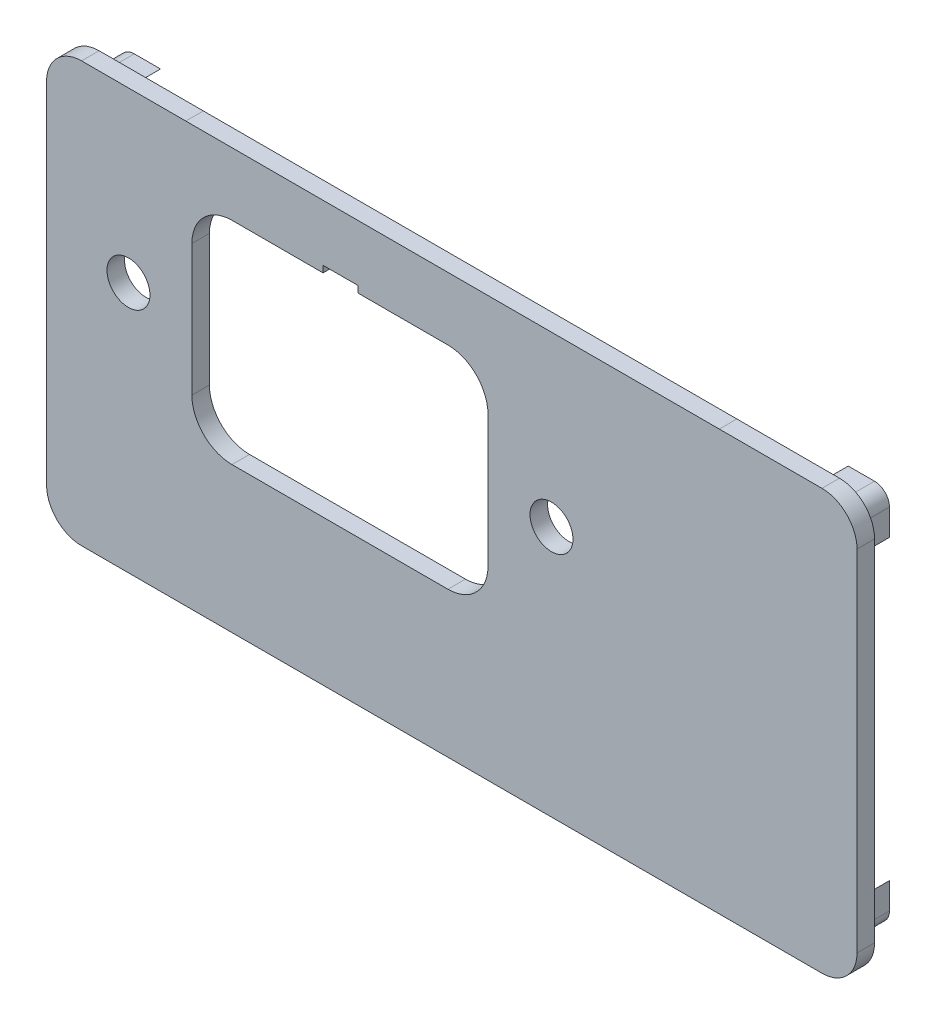
SolidWorks part; units mm, degrees
ref_plane "Front Plane" through (0, 0, 0) normal (0, 0, 1) x (1, 0, 0)
ref_plane "Top Plane" through (0, 0, 0) normal (0, 1, 0) x (1, 0, 0)
ref_plane "Right Plane" through (0, 0, 0) normal (1, 0, 0) x (0, 0, -1)
sketch "Sketch1" plane through (0, 0, 0) normal (0, 0, 1) x (1, 0, 0)
  line L6 (9.1686, 76.7653) -> (-2.7153, 76.7653)
  line L7 (70.0331, 76.7655) -> (9.1686, 76.7653)
  line L8 (81.7397, 76.7655) -> (70.0331, 76.7655)
  line L9 (85.7397, 32.8565) -> (85.7397, 72.7655)
  line L10 (-2.7153, 28.8565) -> (81.7397, 28.8565)
  line L11 (-6.7153, 72.7653) -> (-6.7153, 32.8565)
  line L18 (36.0228, 69.5903) -> (39.0739, 69.5903)
  line L19 (43.6459, 65.0183) -> (43.6459, 50.0323)
  line L20 (39.0739, 45.4603) -> (36.0228, 45.4603)
  line L21 (17.487, 45.4603) -> (14.4359, 45.4603)
  line L22 (9.8639, 50.0323) -> (9.8639, 65.0183)
  line L23 (14.4359, 69.5903) -> (17.487, 69.5903)
  line L24 (17.487, 69.5903) -> (24.826, 69.5903)
  line L25 (36.0228, 45.4603) -> (17.487, 45.4603)
  line L27 (24.826, 69.5903) -> (24.826, 70.3403)
  line L28 (24.826, 70.3403) -> (28.826, 70.3403)
  line L29 (28.826, 70.3403) -> (28.826, 69.5903)
  line L30 (28.826, 69.5903) -> (36.0228, 69.5903)
  circle A6 centre (50.8849, 57.5253) radius 2.449
  circle A7 centre (2.6249, 57.5253) radius 2.449
  arc A8 (85.7397, 72.7655) -> (81.7397, 76.7655) centre (81.7397, 72.7655) ccw
  arc A9 (81.7397, 28.8565) -> (85.7397, 32.8565) centre (81.7397, 32.8565) ccw
  arc A10 (-6.7153, 32.8565) -> (-2.7153, 28.8565) centre (-2.7153, 32.8565) ccw
  arc A11 (-2.7153, 76.7653) -> (-6.7153, 72.7653) centre (-2.7153, 72.7653) ccw
  arc A16 (43.6459, 65.0183) -> (39.0739, 69.5903) centre (39.0739, 65.0183) ccw
  arc A17 (39.0739, 45.4603) -> (43.6459, 50.0323) centre (39.0739, 50.0323) ccw
  arc A18 (9.8639, 50.0323) -> (14.4359, 45.4603) centre (14.4359, 50.0323) ccw
  arc A19 (14.4359, 69.5903) -> (9.8639, 65.0183) centre (14.4359, 65.0183) ccw
extrude "Boss-Extrude2" add sketch "Sketch1" along normal blind 2
sketch "Sketch2" plane through (0, 0, 0) normal (0, 0, -1) x (-1, 0, 0)
  line L3 (-70.0331, 76.7655) -> (-9.1686, 76.7653) construction
  line L6 (4.4153, 35.8565) -> (4.4153, 32.8565)
  line L8 (-9.1686, 74.4653) -> (2.7153, 74.4653) construction
  line L9 (-70.0331, 76.7655) -> (-9.1686, 76.7653)
  line L10 (-81.7397, 74.4655) -> (-70.0331, 74.4655) construction
  line L11 (4.4153, 72.7653) -> (4.4153, 32.8565) construction
  line L12 (-81.7397, 74.4655) -> (-78.7397, 74.4655)
  line L14 (-0.2847, 74.4653) -> (2.7153, 74.4653)
  line L15 (4.4153, 72.7653) -> (4.4153, 69.7653)
  line L16 (2.7153, 31.1565) -> (-0.2847, 31.1565)
  line L17 (-83.4397, 32.8565) -> (-83.4397, 35.8565)
  line L18 (-81.7397, 74.4655) -> (-78.7397, 74.4655)
  line L19 (-78.7397, 74.4655) -> (-83.4397, 69.7655)
  line L20 (2.7153, 74.4653) -> (-0.2847, 74.4653)
  line L21 (-0.2847, 74.4653) -> (4.4153, 69.7653)
  line L22 (4.4153, 32.8565) -> (4.4153, 35.8565)
  line L23 (4.4153, 35.8565) -> (-0.2847, 31.1565)
  line L24 (-83.4397, 32.8565) -> (-83.4397, 35.8565)
  line L25 (-83.4397, 35.8565) -> (-78.7397, 31.1565)
  line L26 (-83.4397, 69.7655) -> (-83.4397, 72.7655)
  line L27 (-78.7397, 31.1565) -> (-81.7397, 31.1565)
  line L28 (-83.4397, 32.8565) -> (-83.4397, 72.7655) construction
  line L30 (2.7153, 31.1565) -> (-81.7397, 31.1565) construction
  line L31 (2.7153, 28.8565) -> (-81.7397, 28.8565) construction
  line L32 (-85.7397, 32.8565) -> (-85.7397, 72.7655) construction
  line L33 (-81.7397, 76.7655) -> (-70.0331, 76.7655) construction
  line L34 (-70.0331, 74.4655) -> (-9.1686, 74.4653) construction
  line L35 (-9.1686, 76.7653) -> (2.7153, 76.7653) construction
  line L36 (6.7153, 72.7653) -> (6.7153, 32.8565) construction
  arc A8 (4.4153, 72.7653) -> (2.7153, 74.4653) centre (2.7153, 72.7653) ccw
  arc A9 (2.7153, 31.1565) -> (4.4153, 32.8565) centre (2.7153, 32.8565) ccw
  arc A10 (-83.4397, 32.8565) -> (-81.7397, 31.1565) centre (-81.7397, 32.8565) ccw
  arc A11 (-81.7397, 74.4655) -> (-83.4397, 72.7655) centre (-81.7397, 72.7655) ccw
  arc A12 (-85.7397, 32.8565) -> (-81.7397, 28.8565) centre (-81.7397, 32.8565) ccw construction
  arc A13 (-81.7397, 76.7655) -> (-85.7397, 72.7655) centre (-81.7397, 72.7655) ccw construction
  arc A14 (6.7153, 72.7653) -> (2.7153, 76.7653) centre (2.7153, 72.7653) ccw construction
  arc A15 (2.7153, 28.8565) -> (6.7153, 32.8565) centre (2.7153, 32.8565) ccw construction
  dimension "D1" = 2.3
extrude "Boss-Extrude3" add sketch "Sketch2" along normal blind 4 contours L17 A10 L27 L25 | L12 A11 L26 L19 | L16 A9 L6 L23 | L15 A8 L14 L21
